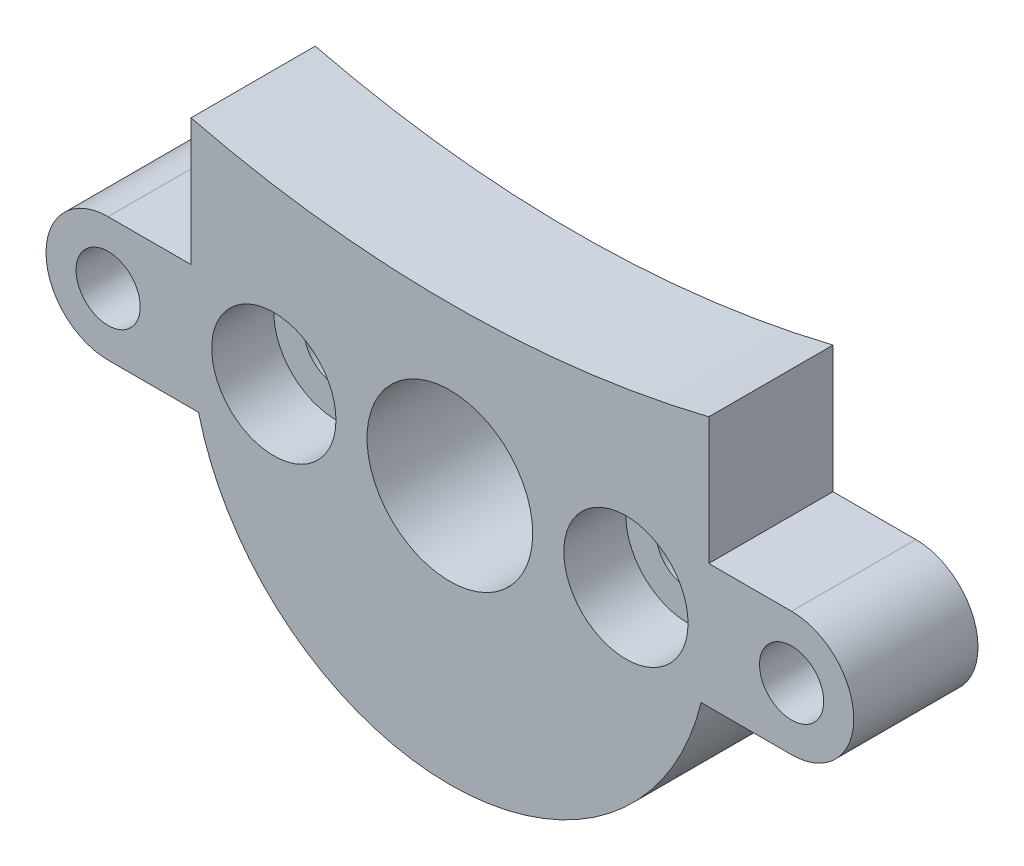
SolidWorks part; units mm, degrees
ref_plane "Front Plane" through (0, 0, 0) normal (0, 0, 1) x (1, 0, 0)
ref_plane "Top Plane" through (0, 0, 0) normal (0, 1, 0) x (1, 0, 0)
ref_plane "Right Plane" through (0, 0, 0) normal (1, 0, 0) x (0, 0, -1)
sketch "Sketch1" plane through (0, 0, 0) normal (0, 0, 1) x (1, 0, 0)
  line L0 (-8.5, 0) -> (8.5, 0) construction
  line L1 (0, 0) -> (0, 60) construction
  line L6 (-8.5, 0) -> (-16.5, 0) construction
  line L7 (8.5, 0) -> (16.5, 0) construction
  line L8 (-16.5, 3) -> (-12.5, 3)
  line L10 (16.5, 3) -> (12.5, 3)
  line L12 (-12.5, 9.1325) -> (-12.5, 3)
  line L13 (12.5, 3) -> (12.5, 9.1325)
  line L14 (16.5, -3) -> (12.1347, -3)
  line L15 (-16.5, -3) -> (-12.1347, -3)
  circle A0 centre (-8.5, 0) radius 1.55
  circle A1 centre (8.5, 0) radius 1.55
  circle A4 centre (0, 60) radius 52.3808 construction
  circle A8 centre (0, 0) radius 4
  arc A16 (-12.5, 0) -> (12.5, 0) centre (0, 0) ccw construction
  arc A17 (-12.5, 9.1325) -> (12.5, 9.1325) centre (0, 60) ccw
  circle A18 centre (-16.5, 0) radius 1.55
  circle A19 centre (16.5, 0) radius 1.55
  arc A21 (-16.5, 3) -> (-16.5, -3) centre (-16.5, 0) ccw
  arc A24 (16.5, 3) -> (16.5, -3) centre (16.5, 0) cw
  arc A25 (-12.1347, -3) -> (12.1347, -3) centre (0, 0) ccw
  point P4 (0, 0)
  point P13 (0, 7.6192)
  point P28 (0, 0)
extrude "Boss-Extrude1" add sketch "Sketch1" along normal blind 6
sketch "Sketch2" plane through (0, 0, 6) normal (0, 0, 1) x (1, 0, 0)
  circle A0 centre (-8.5, 0) radius 3
  circle A1 centre (8.5, 0) radius 3
extrude "Cut-Extrude1" cut sketch "Sketch2" against normal blind 3
